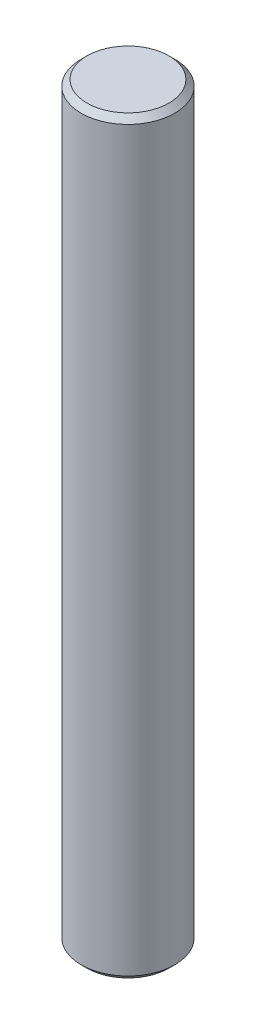
SolidWorks part; units mm, degrees
material "1.4401 (X5CrNiMo17-12-2)"
ref_plane "Front Plane" through (0, 0, 0) normal (0, 0, 1) x (1, 0, 0)
ref_plane "Top Plane" through (0, 0, 0) normal (0, 1, 0) x (1, 0, 0)
ref_plane "Right Plane" through (0, 0, 0) normal (1, 0, 0) x (0, 0, -1)
sketch "Sketch1" plane through (0, 0, 0) normal (0, 1, 0) x (1, 0, 0)
  circle A0 centre (0, 0) radius 2
  dimension "D1" = 4
extrude "Boss-Extrude1" add sketch "Sketch1" along normal mid plane 32
chamfer "Chamfer1" distance 0.25 angle 45 2 edges at (0, -16, 2) (0, 16, 2)
